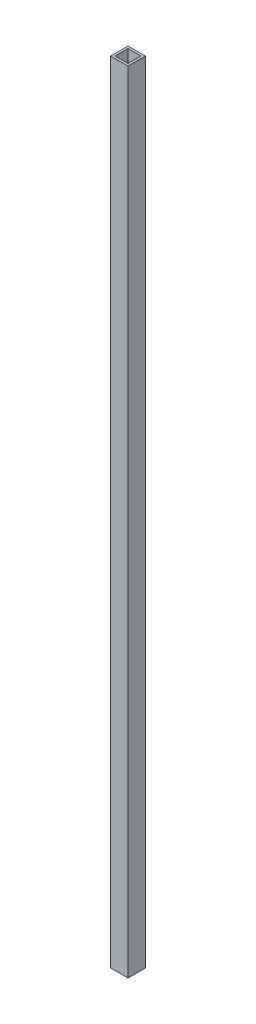
SolidWorks part; units mm, degrees
ref_plane "Piano frontale" through (0, 0, 0) normal (0, 0, 1) x (1, 0, 0)
ref_plane "Piano superiore" through (0, 0, 0) normal (0, 1, 0) x (1, 0, 0)
ref_plane "Piano destro" through (0, 0, 0) normal (1, 0, 0) x (0, 0, -1)
sketch "Schizzo1" plane through (0, 0, 0) normal (0, 1, 0) x (1, 0, 0)
  line L0 (-15, -15) -> (-15, 15)
  line L1 (20, -20) -> (-20, -20)
  line L2 (20, -20) -> (20, 20)
  line L3 (20, 20) -> (-20, 20)
  line L4 (-20, -20) -> (-20, 20)
  line L5 (20, -20) -> (-20, 20) construction
  line L6 (20, 20) -> (-20, -20) construction
  line L7 (15, 15) -> (-15, 15)
  line L8 (15, -15) -> (15, 15)
  line L9 (15, -15) -> (-15, -15)
  point P0 (0, 0)
  dimension "D1" = 40
  dimension "D2" = 40
  dimension "D3" = 5
extrude "Estrusione-Estrusione1" add sketch "Schizzo1" along normal blind 1820
